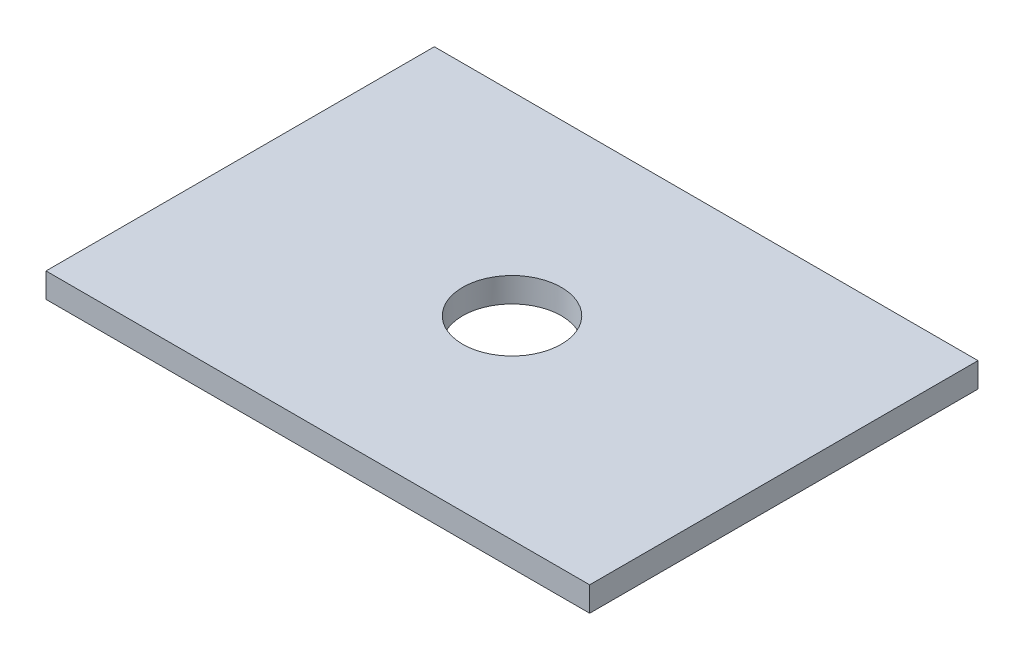
SolidWorks part; units mm, degrees
material "Oak"
ref_plane "Front Plane" through (0, 0, 0) normal (0, 0, 1) x (1, 0, 0)
ref_plane "Top Plane" through (0, 0, 0) normal (0, 1, 0) x (1, 0, 0)
ref_plane "Right Plane" through (0, 0, 0) normal (1, 0, 0) x (0, 0, -1)
sketch "Sketch1" plane through (0, 0, 0) normal (0, 1, 0) x (1, 0, 0)
  line L1 (0, 0) -> (140, 0)
  line L2 (0, 0) -> (0, 100)
  line L3 (0, 100) -> (140, 100)
  line L4 (140, 0) -> (140, 100)
  dimension "D1" = 140
  dimension "D2" = 100
extrude "Boss-Extrude1" add sketch "Sketch1" along normal blind 6.35
sketch "Sketch2" plane through (0, 6.35, 0) normal (0, 1, 0) x (1, 0, 0)
  line L0 (70, 100) -> (70, 0) construction
  line L1 (140, 100) -> (0, 100) construction
  line L2 (0, 0) -> (140, 0) construction
  line L3 (0, 50) -> (140, 50) construction
  line L4 (0, 100) -> (0, 0) construction
  line L5 (140, 0) -> (140, 100) construction
  circle A0 centre (70, 50) radius 12.705
  dimension "D1" = 25.41
extrude "Cut-Extrude1" cut sketch "Sketch2" against normal blind 10
